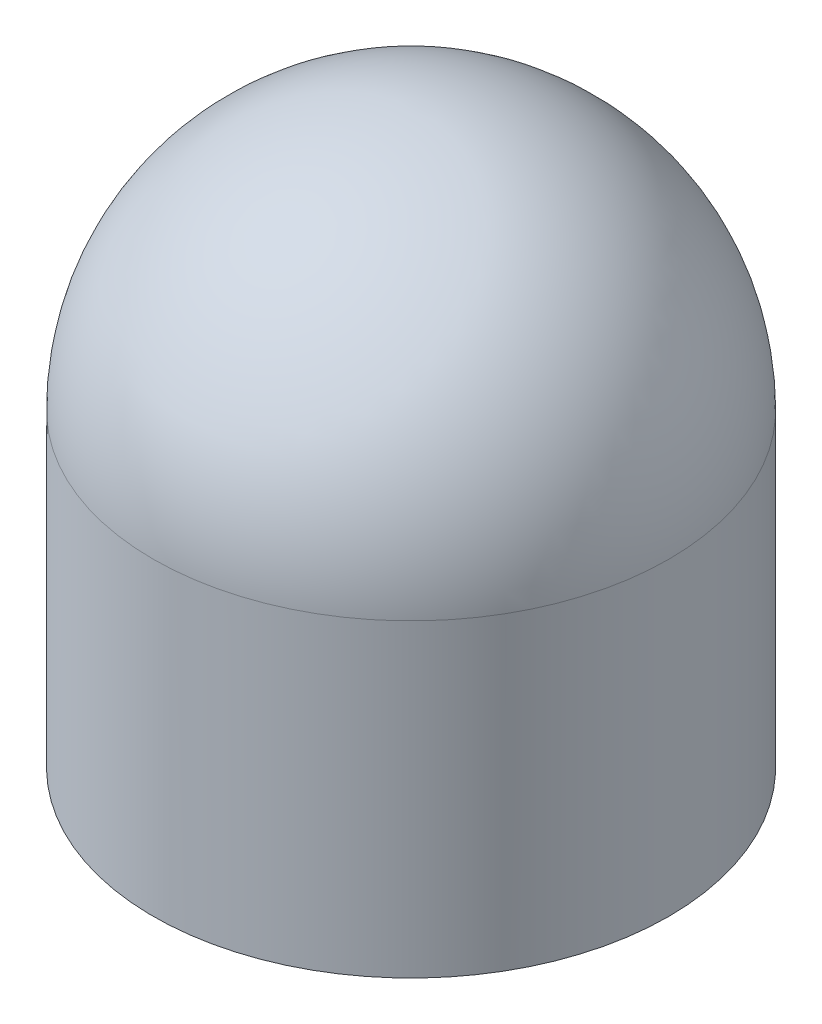
SolidWorks part; units mm, degrees
ref_plane "Front Plane" through (0, 0, 0) normal (0, 0, 1) x (1, 0, 0)
ref_plane "Top Plane" through (0, 0, 0) normal (0, 1, 0) x (1, 0, 0)
ref_plane "Right Plane" through (0, 0, 0) normal (1, 0, 0) x (0, 0, -1)
sketch "Sketch3" plane through (0, 0, 0) normal (0, 0, 1) x (1, 0, 0)
  line L0 (0, 0) -> (5, 0)
  line L1 (0, 0) -> (0, 5)
  arc A0 (5, 0) -> (0, 5) centre (0, 0) ccw
  dimension "D1" = 5
revolve "Revolve1" add sketch "Sketch3" angle 360 about L1
shell "Shell1" thickness 0.1
sketch "Sketch4" plane through (0, 0, 0) normal (0, 0, 1) x (1, 0, 0)
  line L0 (0, 0) -> (5, 0)
  line L1 (5, 0) -> (5, -6)
  line L2 (5, -6) -> (0, -6)
  line L3 (0, -6) -> (0, 0)
  dimension "D1" = 6
revolve "Revolve2" add sketch "Sketch4" angle 360 about L3
